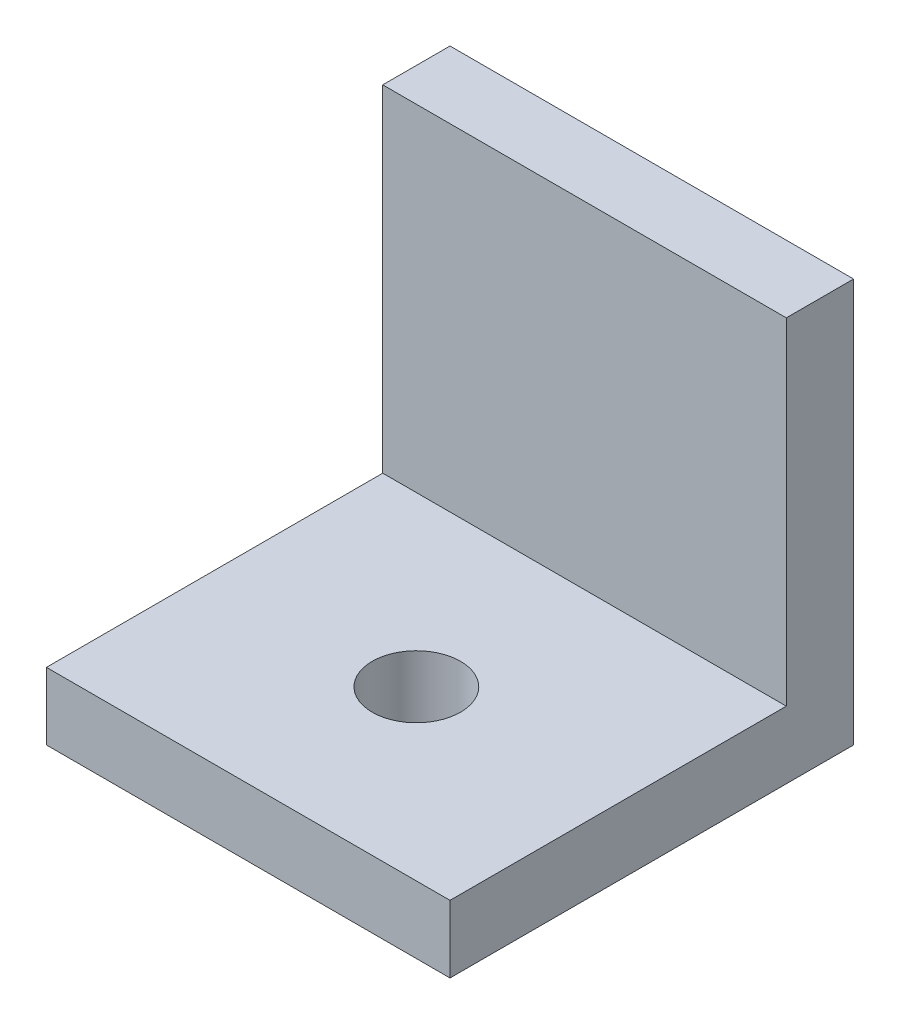
SolidWorks part; units mm, degrees
material "Custom Plastic"
ref_plane "Front Plane" through (0, 0, 0) normal (0, 0, 1) x (1, 0, 0)
ref_plane "Top Plane" through (0, 0, 0) normal (0, 1, 0) x (1, 0, 0)
ref_plane "Right Plane" through (0, 0, 0) normal (1, 0, 0) x (0, 0, -1)
sketch "Sketch2" plane through (0, 0, 0) normal (1, 0, 0) x (0, 0, -1)
  line L0 (0, 0) -> (12.7, 0)
  line L1 (12.7, 0) -> (12.7, -76.2)
  line L2 (12.7, -76.2) -> (-63.5, -76.2)
  line L3 (-63.5, -76.2) -> (-63.5, -63.5)
  line L6 (0, 0) -> (0, -63.5)
  line L7 (0, -63.5) -> (-63.5, -63.5)
extrude "Boss-Extrude1" add sketch "Sketch2" along normal blind 76.2
sketch "Sketch6" plane through (0, -63.5, 0) normal (0, 1, 0) x (1, 0, 0)
  line L1 (76.2, 0) -> (0, 0) construction
  circle A1 centre (38.1, -31.75) radius 8.3344
  dimension "D1" = 31.75
extrude "Cut-Extrude1" cut sketch "Sketch6" against normal blind 12.7
